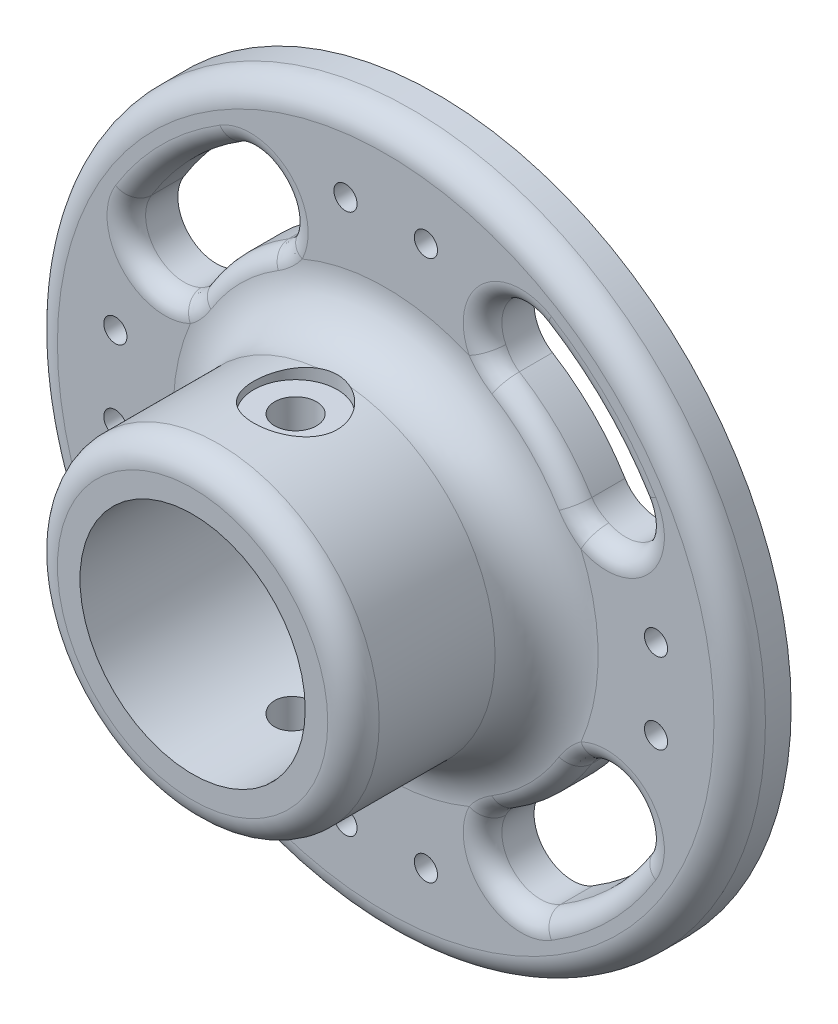
SolidWorks part; units mm, degrees
ref_plane "Front Plane" through (0, 0, 0) normal (0, 0, 1) x (1, 0, 0)
ref_plane "Top Plane" through (0, 0, 0) normal (0, 1, 0) x (1, 0, 0)
ref_plane "Right Plane" through (0, 0, 0) normal (1, 0, 0) x (0, 0, -1)
sketch "Sketch1" plane through (0, 0, 0) normal (0, 0, 1) x (1, 0, 0)
  line L0 (0, 55) -> (0, -55) construction
  line L1 (-55, 0) -> (55, 0) construction
  line L2 (-16.582, 42) -> (18.4897, 42) construction
  line L3 (0, 0) -> (-38.8909, 38.8909) construction
  circle A0 centre (0, 0) radius 55
  circle A1 centre (0, 0) radius 30 construction
  circle A3 centre (-6.25, 42) radius 1.8
  circle A4 centre (6.25, 42) radius 1.8
  circle A5 centre (42, -6.25) radius 1.8
  circle A6 centre (42, 6.25) radius 1.8
  circle A7 centre (-6.25, -42) radius 1.8
  circle A8 centre (6.25, -42) radius 1.8
  circle A9 centre (-42, 6.25) radius 1.8
  circle A10 centre (-42, -6.25) radius 1.8
  arc A11 (-34.2953, 21.0486) -> (-21.0486, 34.2953) centre (0, 0) cw construction
  arc A12 (-24.1872, 39.4089) -> (-39.4089, 24.1872) centre (0, 0) ccw
  arc A13 (-17.9101, 29.1816) -> (-29.1816, 17.9101) centre (0, 0) ccw
  arc A14 (-17.9101, 29.1816) -> (-24.1872, 39.4089) centre (-21.0486, 34.2953) ccw
  arc A15 (-39.4089, 24.1872) -> (-29.1816, 17.9101) centre (-34.2953, 21.0486) ccw
  arc A16 (21.0486, 34.2953) -> (34.2953, 21.0486) centre (0, 0) cw construction
  arc A17 (39.4089, 24.1872) -> (24.1872, 39.4089) centre (0, 0) ccw
  arc A18 (29.1816, 17.9101) -> (17.9101, 29.1816) centre (0, 0) ccw
  arc A19 (29.1816, 17.9101) -> (39.4089, 24.1872) centre (34.2953, 21.0486) ccw
  arc A20 (24.1872, 39.4089) -> (17.9101, 29.1816) centre (21.0486, 34.2953) ccw
  arc A21 (34.2953, -21.0486) -> (21.0486, -34.2953) centre (0, 0) cw construction
  arc A22 (24.1872, -39.4089) -> (39.4089, -24.1872) centre (0, 0) ccw
  arc A23 (17.9101, -29.1816) -> (29.1816, -17.9101) centre (0, 0) ccw
  arc A24 (17.9101, -29.1816) -> (24.1872, -39.4089) centre (21.0486, -34.2953) ccw
  arc A25 (39.4089, -24.1872) -> (29.1816, -17.9101) centre (34.2953, -21.0486) ccw
  arc A26 (-21.0486, -34.2953) -> (-34.2953, -21.0486) centre (0, 0) cw construction
  arc A27 (-39.4089, -24.1872) -> (-24.1872, -39.4089) centre (0, 0) ccw
  arc A28 (-29.1816, -17.9101) -> (-17.9101, -29.1816) centre (0, 0) ccw
  arc A29 (-29.1816, -17.9101) -> (-39.4089, -24.1872) centre (-34.2953, -21.0486) ccw
  arc A30 (-24.1872, -39.4089) -> (-17.9101, -29.1816) centre (-21.0486, -34.2953) ccw
  point P5 (0, 0)
  point P17 (-28.4536, 28.4536)
  point P30 (0, 0)
  point P37 (-28.9986, 28.9986)
  point P38 (-31.3503, 31.3503)
  point P39 (-26.7989, 26.7989)
  point P42 (28.4536, 28.4536)
  point P49 (28.4536, -28.4536)
  point P56 (-28.4536, -28.4536)
  point P61 (0, 0)
  point P62 (-28.477, 28.477)
  point P63 (21.0486, 34.2953)
  dimension "D1" = 42
  dimension "D2" = 12
  dimension "D3" = 110
  dimension "D4" = 12.5
  dimension "D8" = 4
  dimension "D5" = 6.25
  dimension "D7" = 45
  dimension "D6" = 4
extrude "Boss-Extrude1" add sketch "Sketch1" along normal blind 8
sketch "Sketch4" plane through (0, 0, 8) normal (0, 0, 1) x (1, 0, 0)
  circle A1 centre (0, 0) radius 25
  dimension "D1" = 50
extrude "Boss-Extrude3" add sketch "Sketch4" along normal blind 30
fillet "Fillet1" radius 8 1 edges at (25, 0, 8)
sketch "Sketch5" plane through (0, 0, 0) normal (0, 1, 0) x (1, 0, 0)
  line L2 (-25, -38) -> (25, -38) construction
  circle A0 centre (0, -22) radius 3.25
  point P2 (0, -18)
  point P5 (0, 0)
  point P7 (0, 0)
  dimension "D1" = 6.5
  dimension "D2" = 16
extrude "Cut-Extrude1" cut sketch "Sketch5" against normal mid plane 100
sketch "Sketch6" plane through (0, 0, 0) normal (0, 0, -1) x (-1, 0, 0)
  circle A0 centre (0, 0) radius 14
extrude "Cut-Extrude2" cut sketch "Sketch6" against normal through all contours A0
sketch "Sketch7" plane through (0, 0, 38) normal (0, 0, 1) x (1, 0, 0)
  circle A0 centre (0, 0) radius 17.5
extrude "Cut-Extrude3" cut sketch "Sketch7" against normal blind 34
fillet "Fillet2" radius 4 2 edges at (55, 0, 8) (25, 0, 38)
ref_plane "Plane1" through (0, -23, 0) normal (0, 1, 0) x (1, 0, 0)
sketch "Sketch8" plane through (0, -23, 0) normal (0, 1, 0) x (1, 0, 0)
  circle A0 centre (0, -22) radius 6.5
  point P3 (0, 0)
  point P4 (0, -18)
  point P5 (0, -22)
  point P7 (0, 0)
extrude "Cut-Extrude4" cut sketch "Sketch8" against normal blind 5 contours A0
mirror "Mirror1" about plane through (0, 0, 0) normal (0, 1, 0) of "Cut-Extrude4"
fillet "Fillet3" radius 3 16 edges at (-15.935, 37.4338, 8) (-24.2109, 24.2109, 8) (-37.4338, 15.935, 8) (32.6962, 32.6962, 8) (37.4338, 15.935, 8) (24.2109, 24.2109, 8) (24.2109, -24.2109, 8) (37.4338, -15.935, 8) (32.6962, -32.6962, 8) (-15.935, -37.4338, 8) (-32.6962, -32.6962, 8) (-37.4338, -15.935, 8) (-32.6962, 32.6962, 8) (15.935, 37.4338, 8) (15.935, -37.4338, 8) (-24.2109, -24.2109, 8)
